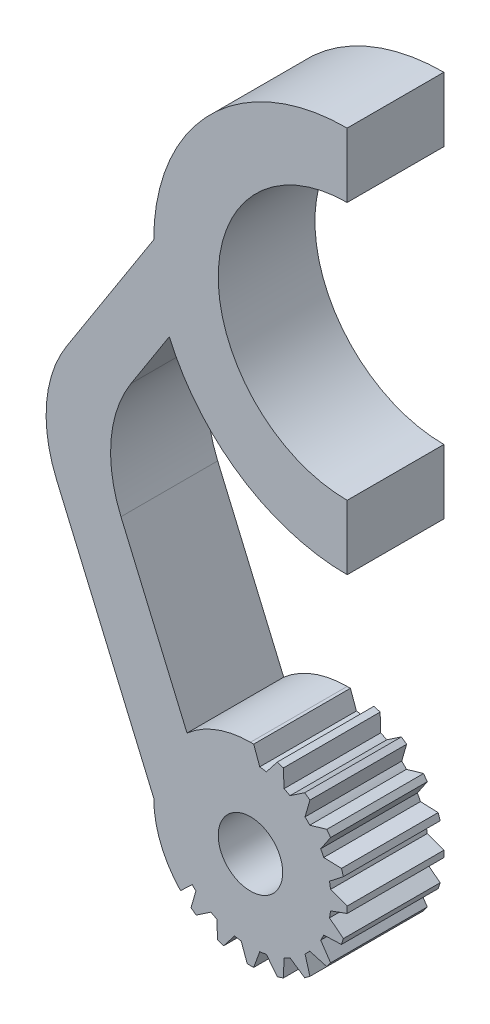
SolidWorks part; units mm, degrees
ref_plane "Front Plane" through (0, 0, 0) normal (0, 0, 1) x (1, 0, 0)
ref_plane "Top Plane" through (0, 0, 0) normal (0, 1, 0) x (1, 0, 0)
ref_plane "Right Plane" through (0, 0, 0) normal (1, 0, 0) x (0, 0, -1)
sketch "Sketch1" plane through (0, 0, 0) normal (0, 0, 1) x (1, 0, 0)
  line L0 (0, 0) -> (0, -120) construction
  line L1 (0, 0) -> (0, -10)
  line L2 (0, -50) -> (0, -60)
  line L4 (-30, -30) -> (-49.2547, -60)
  line L5 (-49.2547, -60) -> (-30, -105)
  line L6 (-20, -30) -> (-39.2547, -60)
  line L7 (-39.2547, -60) -> (-20, -105)
  line L8 (-30, -30) -> (-20, -30)
  line L9 (-30, -105) -> (-20, -105)
  arc A0 (0, -10) -> (0, -50) centre (0, -30) ccw
  arc A1 (0, 0) -> (0, -60) centre (0, -30) ccw
  circle A2 centre (-15, -105) radius 15
  circle A3 centre (-15, -105) radius 5
  dimension "D1" = 40
  dimension "D2" = 60
  dimension "D5" = 15
  dimension "D6" = 15
  dimension "D4" = 120
  dimension "D7" = 10
  dimension "D8" = 15
extrude "Boss-Extrude1" add sketch "Sketch1" along normal blind 15 contours L8 A1 L6 | L1 A1 L8 A0 | L6 A1 L2 A0 | A2 L7 L6 A1 L4 L5 | L7 A2 L9 | L7 A3 L9 A2
fillet "Fillet1" radius 20 2 edges at (-39.2547, -60, 7.5) (-49.2547, -60, 7.5)
sketch "Sketch2" plane through (0, 0, 15) normal (0, 0, 1) x (1, 0, 0)
  line L0 (-15, -90) -> (-15, -92.5)
  line L1 (-25.8458, -115.3619) -> (-24.0381, -113.6349)
  arc A0 (-25.8458, -115.3619) -> (-15, -90) centre (-15, -105) ccw
  arc A1 (-24.0381, -113.6349) -> (-15, -92.5) centre (-15, -105) ccw
  dimension "D1" = 2.5
  dimension "D2" = 30
extrude "Cut-Extrude1" cut sketch "Sketch2" against normal blind 15
sketch "Sketch3" plane through (0, 0, 15) normal (0, 0, 1) x (1, 0, 0)
  line L0 (-15, -90) -> (-14.5, -90)
  line L3 (-15, -92.75) -> (-15, -90)
  line L4 (-15, -92.75) -> (-13.5, -92.75)
  line L5 (-13.5, -92.75) -> (-14.5, -90)
  line L7 (-12.6411, -92.886) -> (-9.788, -93.8131)
  line L8 (-9.788, -93.8131) -> (-9.8892, -90.8887)
  line L9 (-10.8403, -90.5796) -> (-9.8892, -90.8887)
  line L10 (-12.6411, -92.886) -> (-10.8403, -90.5796)
  line L11 (-9.0132, -94.2079) -> (-6.5861, -95.9712)
  line L12 (-6.5861, -95.9712) -> (-5.7787, -93.1586)
  line L13 (-6.5877, -92.5709) -> (-5.7787, -93.1586)
  line L14 (-9.0132, -94.2079) -> (-6.5877, -92.5709)
  line L15 (-5.9712, -96.5861) -> (-4.2079, -99.0132)
  line L16 (-4.2079, -99.0132) -> (-2.5709, -96.5877)
  line L17 (-3.1586, -95.7787) -> (-2.5709, -96.5877)
  line L18 (-5.9712, -96.5861) -> (-3.1586, -95.7787)
  line L19 (-3.8131, -99.788) -> (-2.886, -102.6411)
  line L20 (-2.886, -102.6411) -> (-0.5796, -100.8403)
  line L21 (-0.8887, -99.8892) -> (-0.5796, -100.8403)
  line L22 (-3.8131, -99.788) -> (-0.8887, -99.8892)
  line L23 (-2.75, -103.5) -> (-2.75, -106.5)
  line L24 (-2.75, -106.5) -> (0, -105.5)
  line L25 (0, -104.5) -> (0, -105.5)
  line L26 (-2.75, -103.5) -> (0, -104.5)
  line L27 (-2.886, -107.3589) -> (-3.8131, -110.212)
  line L28 (-3.8131, -110.212) -> (-0.8887, -110.1108)
  line L29 (-0.5796, -109.1597) -> (-0.8887, -110.1108)
  line L30 (-2.886, -107.3589) -> (-0.5796, -109.1597)
  line L31 (-4.2079, -110.9868) -> (-5.9712, -113.4139)
  line L32 (-5.9712, -113.4139) -> (-3.1586, -114.2213)
  line L33 (-2.5709, -113.4123) -> (-3.1586, -114.2213)
  line L34 (-4.2079, -110.9868) -> (-2.5709, -113.4123)
  line L35 (-6.5861, -114.0288) -> (-9.0132, -115.7921)
  line L36 (-9.0132, -115.7921) -> (-6.5877, -117.4291)
  line L37 (-5.7787, -116.8414) -> (-6.5877, -117.4291)
  line L38 (-6.5861, -114.0288) -> (-5.7787, -116.8414)
  line L39 (-9.788, -116.1869) -> (-12.6411, -117.114)
  line L40 (-12.6411, -117.114) -> (-10.8403, -119.4204)
  line L41 (-9.8892, -119.1113) -> (-10.8403, -119.4204)
  line L42 (-9.788, -116.1869) -> (-9.8892, -119.1113)
  line L43 (-13.5, -117.25) -> (-16.5, -117.25)
  line L44 (-16.5, -117.25) -> (-15.5, -120)
  line L45 (-14.5, -120) -> (-15.5, -120)
  line L46 (-13.5, -117.25) -> (-14.5, -120)
  line L47 (-17.3589, -117.114) -> (-20.212, -116.1869)
  line L48 (-20.212, -116.1869) -> (-20.1108, -119.1113)
  line L49 (-19.1597, -119.4204) -> (-20.1108, -119.1113)
  line L50 (-17.3589, -117.114) -> (-19.1597, -119.4204)
  line L51 (-20.9868, -115.7921) -> (-23.4139, -114.0288)
  line L52 (-23.4139, -114.0288) -> (-24.2213, -116.8414)
  line L53 (-23.4123, -117.4291) -> (-24.2213, -116.8414)
  line L54 (-20.9868, -115.7921) -> (-23.4123, -117.4291)
  line L55 (-24.0288, -113.4139) -> (-25.7921, -110.9868)
  line L56 (-25.7921, -110.9868) -> (-25.8915, -111.134)
  line L58 (-24.0288, -113.4139) -> (-24.1994, -113.4629)
  line L59 (-26.1869, -110.212) -> (-27.114, -107.3589)
  line L60 (-27.114, -107.3589) -> (-27.2539, -107.4681)
  line L62 (-26.1869, -110.212) -> (-26.3644, -110.2059)
  line L63 (-27.25, -106.5) -> (-27.25, -103.5)
  line L64 (-27.25, -103.5) -> (-27.4169, -103.5607)
  line L66 (-27.25, -106.5) -> (-27.4169, -106.4393)
  line L67 (-27.114, -102.6411) -> (-26.1869, -99.788)
  line L68 (-26.1869, -99.788) -> (-26.3644, -99.7941)
  line L70 (-27.114, -102.6411) -> (-27.2539, -102.5319)
  line L71 (-25.7921, -99.0132) -> (-24.0288, -96.5861)
  line L72 (-24.0288, -96.5861) -> (-24.1994, -96.5371)
  line L74 (-25.7921, -99.0132) -> (-25.8915, -98.866)
  line L83 (-27.4291, -96.5877) -> (-26.8414, -95.7787) [skipped]
  line L84 (-24.2213, -93.1586) -> (-23.4123, -92.5709) [skipped]
  line L85 (-20.1108, -90.8887) -> (-19.1597, -90.5796) [skipped]
  line L86 (-29.4204, -100.8403) -> (-29.1113, -99.8892) [skipped]
  line L87 (-30, -105.5) -> (-30, -104.5) [skipped]
  line L88 (-26.8414, -114.2213) -> (-27.4291, -113.4123) [skipped]
  line L89 (-29.1113, -110.1108) -> (-29.4204, -109.1597) [skipped]
  line L90 (-17.3589, -92.886) -> (-17.4681, -92.7461) [skipped]
  line L91 (-20.212, -93.8131) -> (-17.3589, -92.886) [skipped]
  line L92 (-20.9868, -94.2079) -> (-21.134, -94.1085) [skipped]
  line L93 (-23.4139, -95.9712) -> (-20.9868, -94.2079) [skipped]
  circle A0 centre (-15, -105) radius 12.5
  arc M18 (-24.0381, -113.6349) -> (-15, -92.5) centre (-15, -105) ccw
  line M19 (-15, -92.5) -> (-15, -90)
  dimension "D1" = 20
extrude "Boss-Extrude2" add sketch "Sketch3" against normal blind 15 contours L3 A0 L72 L71 L74 L68 L67 L70 L64 L63 L66 L60 L59 L62 L56 L55 L58 L52 L51 L54 L48 L47 L50 L44 L43 L46 L40 L39 L42 L36 L35 L38 L32 L31 L34 L28 L27 L30 M18 | L18 L16 L17 M18 | L5 L0 M18 M19 | L22 L20 L21 M18 | L10 L8 L9 M18 | L26 L24 L25 M18 | L14 L12 L13 M18 | L30 L28 L29 M18 | L34 L32 L33 M18 | L38 L36 L37 M18 | L46 L44 L45 M18 | L54 L52 L53 M18
